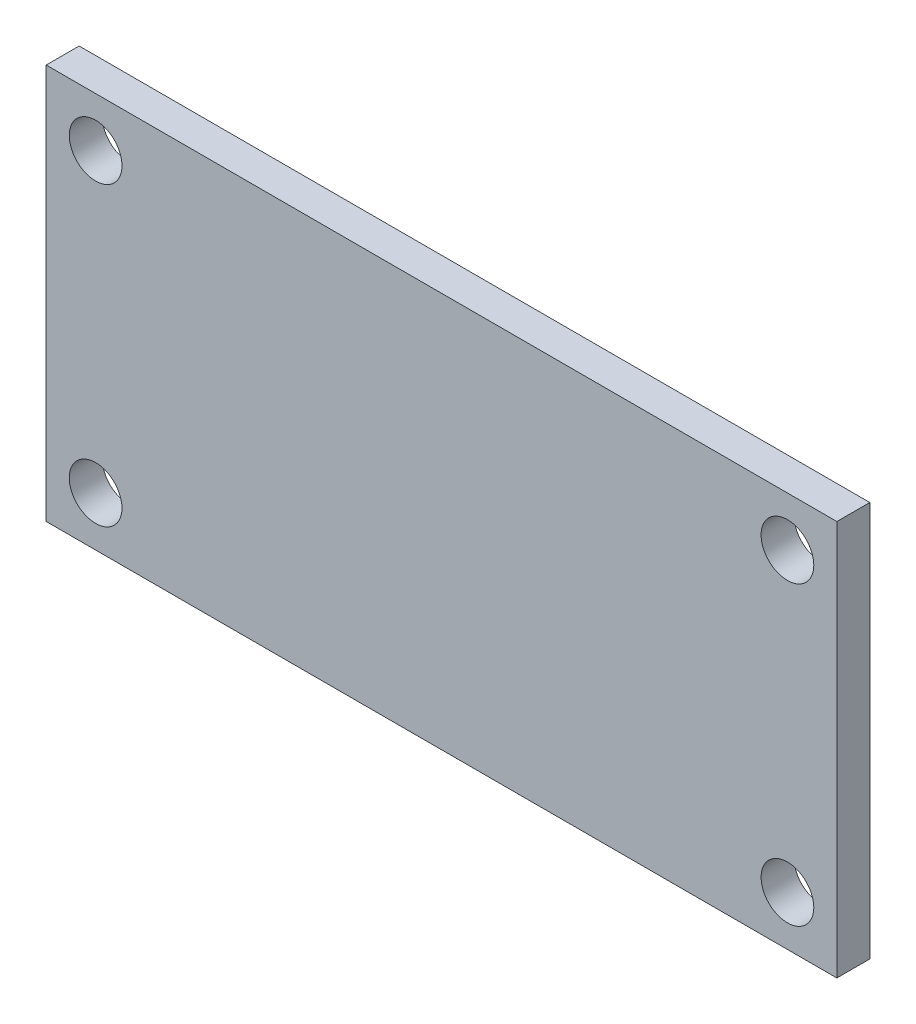
SolidWorks part; units mm, degrees
ref_plane "前视基准面" through (0, 0, 0) normal (0, 0, 1) x (1, 0, 0)
ref_plane "上视基准面" through (0, 0, 0) normal (0, 1, 0) x (1, 0, 0)
ref_plane "右视基准面" through (0, 0, 0) normal (1, 0, 0) x (0, 0, -1)
other "Configuration Table"
sketch "草图1" plane through (0, 0, 0) normal (0, 0, 1) x (1, 0, 0)
  line L0 (3, 21) -> (3, 3) construction
  line L1 (0, 0) -> (48, 0)
  line L2 (0, 0) -> (0, 24)
  line L3 (0, 24) -> (48, 24)
  line L4 (48, 0) -> (48, 24)
  line L5 (3, 3) -> (45, 3) construction
  circle A0 centre (3, 3) radius 1.6
  circle A1 centre (3, 21) radius 1.6
  circle A2 centre (45, 21) radius 1.6
  circle A3 centre (45, 3) radius 1.6
  dimension "D3" = 3.2
  dimension "D1" = 24
  dimension "D2" = 48
  dimension "D4" = 42
  dimension "D5" = 42
  dimension "D6" = 18
  dimension "D7" = 18
  dimension "D8" = 3
  dimension "D9" = 3
extrude "凸台-拉伸1" add sketch "草图1" along normal blind 2
